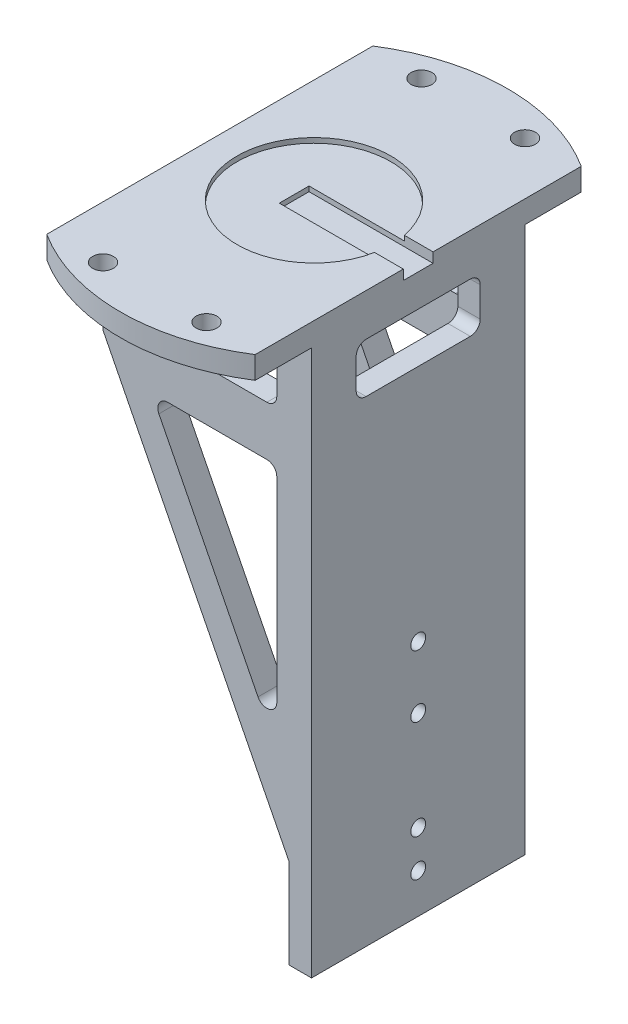
SolidWorks part; units mm, degrees
ref_plane "Front Plane" through (0, 0, 0) normal (0, 0, 1) x (1, 0, 0)
ref_plane "Top Plane" through (0, 0, 0) normal (0, 1, 0) x (1, 0, 0)
ref_plane "Right Plane" through (0, 0, 0) normal (1, 0, 0) x (0, 0, -1)
sketch "Sketch1" plane through (0, 0, 0) normal (0, 1, 0) x (1, 0, 0)
  line L0 (-33.75, 0) -> (0, 0) construction
  line L1 (0, 0) -> (-19.5, 33.775)
  line L2 (0, 0) -> (19.5, 33.775)
  line L3 (0, 0) -> (0, 39) construction
  line L4 (0, 0) -> (-19.5, -33.775)
  line L5 (0, 0) -> (19.5, -33.775)
  line L6 (-21, 36.3731) -> (-21, -36.3731)
  line L7 (21, 36.3731) -> (21, -36.3731)
  circle A0 centre (0, 0) radius 39
  circle A1 centre (-33.75, 0) radius 2.1
  circle A2 centre (-27.3043, 19.8378) radius 2.1
  circle A3 centre (-10.4293, 32.0982) radius 2.1
  circle A4 centre (10.4293, 32.0982) radius 2.1
  circle A5 centre (27.3043, 19.8378) radius 2.1
  circle A6 centre (33.75, 0) radius 2.1
  circle A7 centre (27.3043, -19.8378) radius 2.1
  circle A8 centre (10.4293, -32.0982) radius 2.1
  circle A9 centre (-10.4293, -32.0982) radius 2.1
  circle A10 centre (-27.3043, -19.8378) radius 2.1
  dimension "D1" = 78
  dimension "D3" = 4.2
  dimension "D2" = 33.75
  dimension "D5" = 30
  dimension "D6" = 30
  dimension "D7" = 30
  dimension "D8" = 30
  dimension "D9" = 42
  dimension "D10" = 21
  dimension "D4" = 10
extrude "Boss-Extrude1" add sketch "Sketch1" along normal blind 4.5 contours L4 A0 L5 A9 A8 | L7 L2 L5 | L2 A0 L1 A4 A3 | L1 L6 L4
sketch "Sketch2" plane through (0, 4.5, 0) normal (0, 1, 0) x (1, 0, 0)
  circle A0 centre (0, 0) radius 15.5
  dimension "D1" = 31
extrude "Cut-Extrude1" cut sketch "Sketch2" against normal blind 1
sketch "Sketch3" plane through (0, 4.5, 0) normal (0, 1, 0) x (1, 0, 0)
  line L0 (21, 32.8634) -> (21, -32.8634) construction
  line L1 (21, 3) -> (-4, 3)
  line L2 (21, 3) -> (21, -3)
  line L3 (21, -3) -> (-4, -3)
  line L4 (-4, 3) -> (-4, -3)
  dimension "D2" = 6
  dimension "D3" = 3
  dimension "D4" = 4
extrude "Cut-Extrude2" cut sketch "Sketch3" against normal blind 2
sketch "Sketch4" plane through (0, 0, 0) normal (0, -1, 0) x (1, 0, 0)
  line L0 (-21.5, 21.5) -> (21.5, 21.5)
  line L1 (-21.5, -16.5) -> (16.5, -16.5)
  line L2 (-16.5, -16.5) -> (-16.5, 16.5)
  line L3 (-21.5, 16.5) -> (16.5, 16.5)
  line L4 (16.5, -16.5) -> (16.5, 16.5)
  line L5 (-16.5, -16.5) -> (16.5, 16.5) construction
  line L6 (-16.5, 16.5) -> (16.5, -16.5) construction
  line L7 (21.5, -21.5) -> (21.5, 21.5)
  line L8 (-21.5, -21.5) -> (21.5, -21.5)
  line L9 (-21.5, -21.5) -> (-21.5, 21.5)
  line L11 (-16.5, 16.5) -> (16.5, 16.5) construction
  line L12 (-16.5, -16.5) -> (16.5, -16.5) construction
  point P0 (0, 0)
  line M10 (21, -32.8634) -> (21, 32.8634)
  line M12 (-21, 32.8634) -> (-21, -32.8634)
  dimension "D1" = 33
  dimension "D2" = 5
  dimension "D3" = 33
extrude "Boss-Extrude2" add sketch "Sketch4" along normal blind 110 contours L8 L0 L3 L4 L1 M12 M10
sketch "Sketch5" plane through (0, 0, 21.5) normal (0, 0, 1) x (1, 0, 0)
  line L0 (16.5, -110) -> (-21, 0) construction
  line L1 (-21, 0) -> (-21, -110)
  line L2 (-21, -110) -> (16.5, -110)
  line L3 (-21, -18) -> (16.5, -110) construction
  line L4 (-21, 0) -> (21, 0) construction
  line L5 (16.5, -110) -> (16.5, -92)
  line L6 (16.5, -92) -> (21, -92)
  line L7 (21, -110) -> (21, 0) construction
  line L8 (-21, -18) -> (16.5, -92)
  line M3 (-21, -110) -> (21, -110)
  dimension "D1" = 18
  dimension "D2" = 18
extrude "Cut-Extrude3" cut sketch "Sketch5" against normal through all contours L3 L1 M3
sketch "Sketch6" plane through (21, 0, 0) normal (1, 0, 0) x (0, 0, -1)
  line L0 (21.5, -110) -> (-21.5, -110) construction
  circle A0 centre (0, -102) radius 1.5
  circle A1 centre (0, -94.5) radius 1.5
  circle A2 centre (0, -74.5) radius 1.5
  circle A3 centre (0, -62) radius 1.5
  dimension "D1" = 3
  dimension "D2" = 3
  dimension "D3" = 3
  dimension "D4" = 3
  dimension "D5" = 8
  dimension "D6" = 7.5
  dimension "D7" = 35.5
  dimension "D8" = 12.5
extrude "Cut-Extrude4" cut sketch "Sketch6" against normal up to next
sketch "Sketch7" plane through (16.5, 0, 0) normal (-1, 0, 0) x (0, 0, 1)
  line L0 (-10.5, -4) -> (10.5, -4)
  line L1 (-16.5, 0) -> (16.5, 0) construction
  line L2 (-16.5, 0) -> (-16.5, -18) construction
  line L3 (-16.5, -18) -> (16.5, -18) construction
  line L4 (16.5, 0) -> (16.5, -18) construction
  line L5 (-16.5, 0) -> (16.5, -18) construction
  line L6 (-16.5, -18) -> (16.5, 0) construction
  line L7 (12.5, -6) -> (12.5, -12)
  line L8 (-10.5, -14) -> (10.5, -14)
  line L9 (-12.5, -6) -> (-12.5, -12)
  line L10 (-12.5, -4) -> (-12.5, -14) construction
  line L11 (-12.5, -14) -> (12.5, -14) construction
  line L12 (12.5, -4) -> (12.5, -14) construction
  line L13 (-12.5, -4) -> (12.5, -4) construction
  arc A0 (-12.5, -12) -> (-10.5, -14) centre (-10.5, -12) ccw
  arc A1 (10.5, -14) -> (12.5, -12) centre (10.5, -12) ccw
  arc A2 (12.5, -6) -> (10.5, -4) centre (10.5, -6) ccw
  arc A3 (-10.5, -4) -> (-12.5, -6) centre (-10.5, -6) ccw
  point P4 (0, -9)
  dimension "D2" = 2
  dimension "D1" = 4
extrude "Cut-Extrude5" cut sketch "Sketch7" against normal up to next
sketch "Sketch8" plane through (0, 0, 21.5) normal (0, 0, 1) x (1, 0, 0)
  line L1 (21, 0) -> (-21, 0) construction
  line L2 (21, 0) -> (21, -18) construction
  line L3 (21, -18) -> (-21, -18) construction
  line L4 (-21, 0) -> (-21, -18) construction
  line L5 (21, 0) -> (-21, -18) construction
  line L6 (21, -18) -> (-21, 0) construction
  line L10 (-7.9774, -24) -> (12, -24)
  line L11 (-12, -14) -> (12, -14)
  line L12 (-14, -12) -> (-14, -6)
  line L13 (-12, -4) -> (12, -4)
  line L14 (-21, -18) -> (16.5, -18)
  line L15 (-21, -18) -> (16.5, -92)
  line L16 (16.5, -92) -> (16.5, -18)
  line L21 (-9.7614, -26.9041) -> (10.216, -66.3261)
  line L23 (14, -12) -> (14, -6)
  line L24 (-14, -14) -> (14, -4) construction
  line L25 (-14, -4) -> (14, -14) construction
  line L26 (-11.233, -24) -> (10.5, -24) construction
  line L27 (-11.233, -24) -> (10.5, -66.8865) construction
  line L28 (10.5, -66.8865) -> (10.5, -24) construction
  line L29 (14, -26) -> (14, -65.422)
  arc A7 (-14, -12) -> (-12, -14) centre (-12, -12) ccw
  arc A8 (12, -14) -> (14, -12) centre (12, -12) ccw
  arc A9 (14, -6) -> (12, -4) centre (12, -6) ccw
  arc A10 (-12, -4) -> (-14, -6) centre (-12, -6) ccw
  arc A11 (10.216, -66.3261) -> (14, -65.422) centre (12, -65.422) ccw
  arc A12 (12, -24) -> (14, -26) centre (12, -26) cw
  arc A13 (-7.9774, -24) -> (-9.7614, -26.9041) centre (-7.9774, -26) ccw
  point P4 (0, -9)
  point P5 (0, -9)
  point P12 (-21, -9)
  dimension "D2" = 7
  dimension "D4" = 2
  dimension "D5" = 2
  dimension "D1" = 4
  dimension "D3" = 6
extrude "Cut-Extrude6" cut sketch "Sketch8" against normal blind 110
